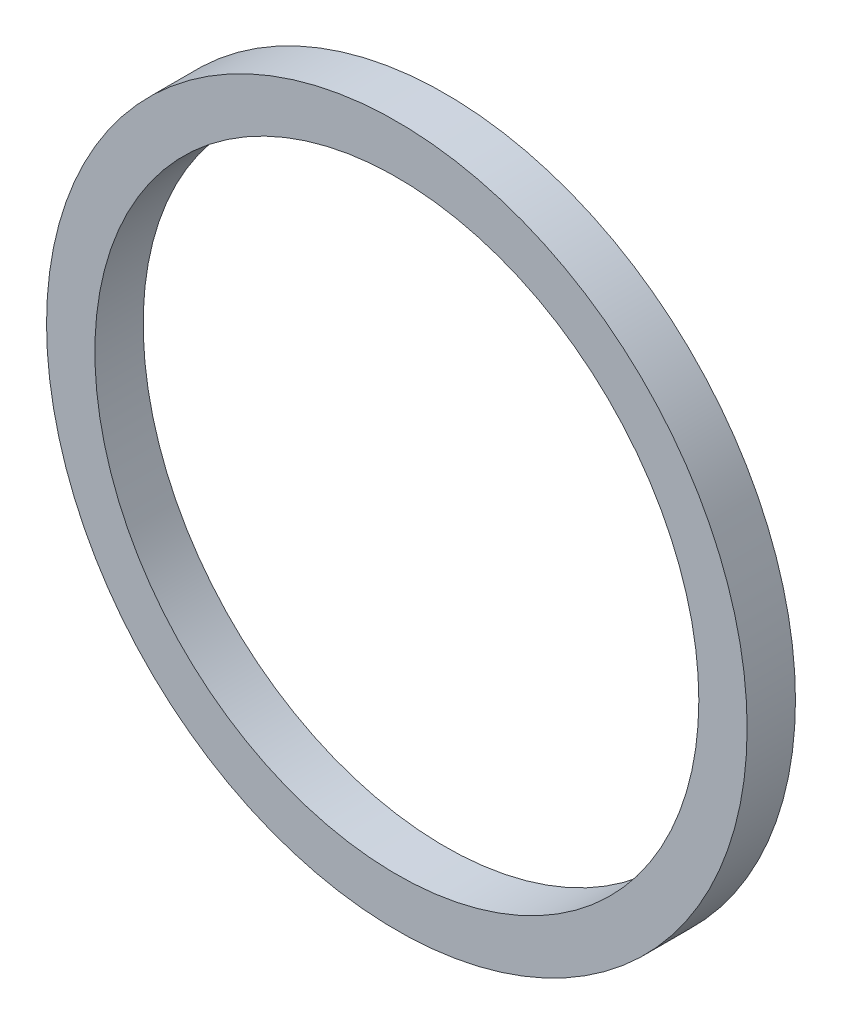
SolidWorks part; units mm, degrees
material "Very Low Density PE (SS)"
ref_plane "Płaszczyzna przednia" through (0, 0, 0) normal (0, 0, 1) x (1, 0, 0)
ref_plane "Płaszczyzna górna" through (0, 0, 0) normal (0, 1, 0) x (1, 0, 0)
ref_plane "Płaszczyzna prawa" through (0, 0, 0) normal (1, 0, 0) x (0, 0, -1)
sketch "Szkic1" plane through (0, 0, 0) normal (0, 0, 1) x (1, 0, 0)
  circle A0 centre (0, 0) radius 62.5
  circle A1 centre (0, 0) radius 72.5
  dimension "D1" = 125
  dimension "D2" = 10
extrude "Dodanie-wyciągnięcie1" add sketch "Szkic1" along normal blind 10
